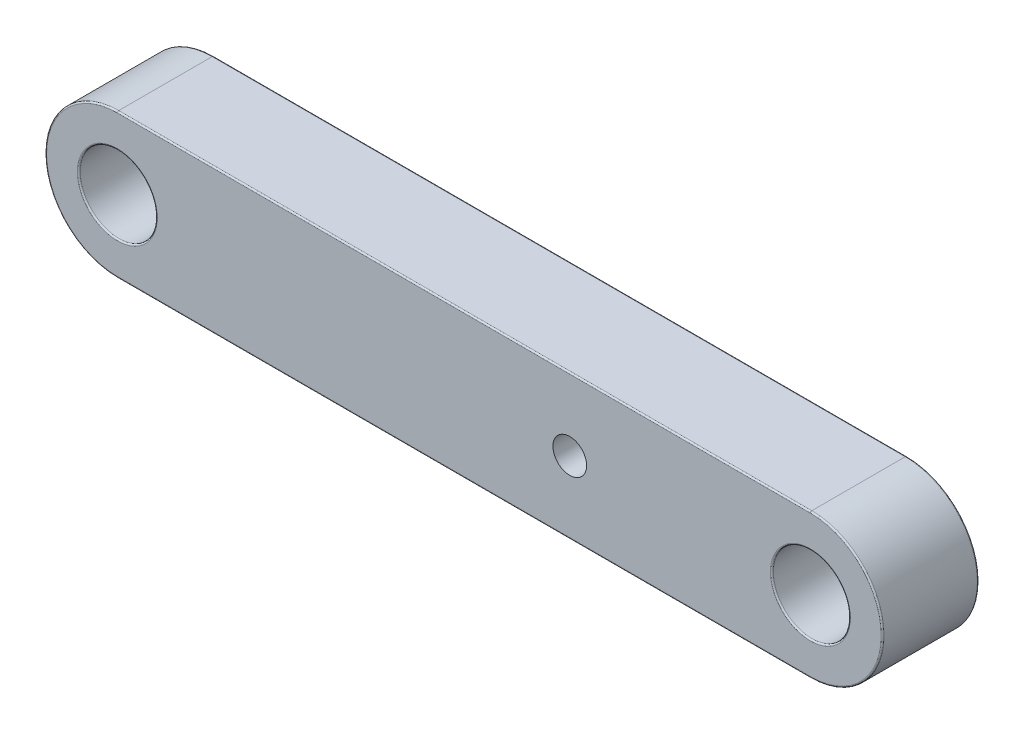
SolidWorks part; units mm, degrees
ref_plane "Front Plane" through (0, 0, 0) normal (0, 0, 1) x (1, 0, 0)
ref_plane "Top Plane" through (0, 0, 0) normal (0, 1, 0) x (1, 0, 0)
ref_plane "Right Plane" through (0, 0, 0) normal (1, 0, 0) x (0, 0, -1)
sketch "Sketch1" plane through (0, 0, 0) normal (0, 0, 1) x (1, 0, 0)
  line L1 (-36, 7.5) -> (36, 7.5) construction
  line L2 (-36, 7.5) -> (-36, -7.5) construction
  line L3 (-36, -7.5) -> (36, -7.5) construction
  line L4 (36, 7.5) -> (36, -7.5) construction
  line L5 (-36, 7.5) -> (36, -7.5) construction
  line L6 (-36, -7.5) -> (36, 7.5) construction
  line L7 (-36, 7.5) -> (36, 7.5)
  line L9 (-36, -7.5) -> (36, -7.5)
  line L11 (-36, 7.5) -> (36, -7.5) construction
  line L12 (-36, -7.5) -> (36, 7.5) construction
  arc A0 (-36, 7.5) -> (-36, -7.5) centre (-36, 0) ccw
  arc A1 (36, -7.5) -> (36, 7.5) centre (36, 0) ccw
  circle A2 centre (-36, 0) radius 4
  circle A3 centre (36, 0) radius 4
  point P0 (0, 0)
  point P12 (0, 0)
  dimension "D3" = 8
  dimension "D1" = 72
  dimension "D2" = 15
  dimension "D4" = 15
extrude "Boss-Extrude1" add sketch "Sketch1" along normal mid plane 10
fillet "Fillet2" radius 0.15 12 edges at (40, 0, -5) (-32, 0, -5) (0, 7.5, -5) (-43.5, 0, -5) (0, -7.5, -5) (43.5, 0, -5) (40, 0, 5) (-43.5, 0, 5) (0, 7.5, 5) (43.5, 0, 5) (0, -7.5, 5) (-32, 0, 5)
sketch "Sketch2" plane through (0, 0, -5) normal (0, 0, -1) x (-1, 0, 0)
  line L0 (-36, 7.5) -> (36, 7.5) construction
  line L1 (-16, 4) -> (-6, 4)
  line L2 (-16, 4) -> (-16, -3.9994)
  line L3 (-16, -3.9994) -> (-6, -3.9994)
  line L4 (-6, 4) -> (-6, -3.9994)
  line L5 (36, -7.5) -> (-36, -7.5) construction
  circle A0 centre (-36, 0) radius 4.15 construction
  dimension "D3" = 20
  dimension "D1" = 3.5
  dimension "D2" = 3.5006
  dimension "D4" = 30
extrude "Cut-Extrude1" cut sketch "Sketch2" against normal blind 3
sketch "Sketch3" plane through (0, 0, -2) normal (0, 0, -1) x (-1, 0, 0)
  line L0 (-16, 4) -> (-6, -3.9994) construction
  line L1 (-16, -3.9994) -> (-6, 4) construction
  circle A0 centre (-11, 0.0003) radius 1.75
  dimension "D1" = 3.5
extrude "Cut-Extrude2" cut sketch "Sketch3" against normal through all
